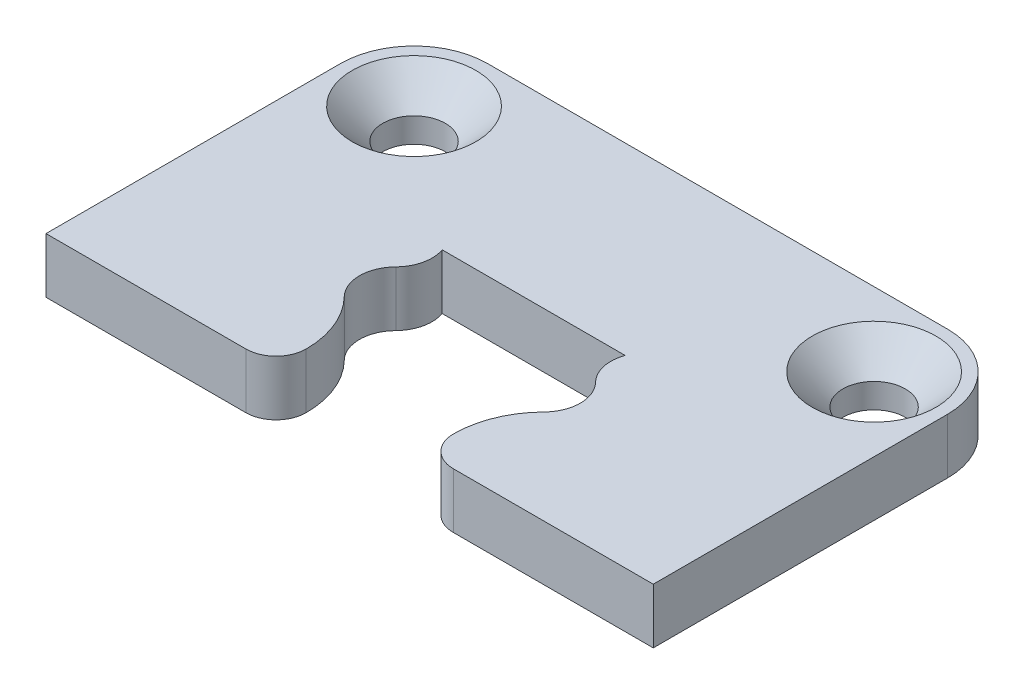
SolidWorks part; units mm, degrees
ref_plane "Front" through (0, 0, 0) normal (0, 0, 1) x (1, 0, 0)
ref_plane "Top" through (0, 0, 0) normal (0, 1, 0) x (1, 0, 0)
ref_plane "Right" through (0, 0, 0) normal (1, 0, 0) x (0, 0, -1)
sketch "Sketch1" plane through (0, 0, 0) normal (0, 1, 0) x (1, 0, 0)
  line L1 (-16.5, 20) -> (16.5, 20)
  line L2 (-16.5, 20) -> (-16.5, 0)
  line L3 (-16.5, 0) -> (-5.6369, 0)
  line L4 (16.5, 20) -> (16.5, 0)
  line L7 (5.6369, 0) -> (16.5, 0)
  line L8 (-5.6369, 0) -> (5.6369, 0) construction
  line L9 (0, 0) -> (0, 10) construction
  line L10 (-4.9708, 10) -> (4.9708, 10)
  line L11 (-4, 6.5359) -> (-4, 0) construction
  arc A0 (-5.4286, 5.1362) -> (-5.4286, 7.9356) centre (-4, 6.5359) cw
  arc A3 (-4, 1.6369) -> (-5.4286, 5.1362) centre (-9, 1.6369) ccw
  arc A4 (-5.4286, 7.9356) -> (-4.9708, 10) centre (-6.8571, 9.3353) ccw
  arc A7 (4, 1.6369) -> (5.4286, 5.1362) centre (9, 1.6369) cw
  arc A8 (5.4286, 5.1362) -> (5.4286, 7.9356) centre (4, 6.5359) ccw
  arc A9 (5.4286, 7.9356) -> (4.9708, 10) centre (6.8571, 9.3353) cw
  arc A10 (-5.4286, 7.9356) -> (-5, 8.2679) centre (-4, 6.5359) cw construction
  arc A11 (-5, 8.2679) -> (-4, 10) centre (-6, 10) ccw construction
  arc A12 (-5.6369, 0) -> (-4, 1.6369) centre (-5.6369, 1.6369) ccw
  arc A13 (5.6369, 0) -> (4, 1.6369) centre (5.6369, 1.6369) cw
  dimension "D3" = 5
  dimension "D4" = 2
  dimension "D6" = 10
  dimension "D1" = 20
  dimension "D2" = 33
  dimension "D5" = 8
extrude "Boss-Extrude1" add sketch "Sketch1" along normal blind 3
sketch "Sketch2" plane through (0, 0, 0) normal (0, 1, 0) x (1, 0, 0)
  line L0 (-12.5, 16) -> (12.5, 16) construction
  line L3 (0, 16) -> (0, 0) construction
  line L4 (16.5, 20) -> (-16.5, 20) construction
  dimension "D1" = 25
  dimension "D2" = 4
hole_wizard "CSK for M3 SFHCS1" positions "Sketch3" profile "Sketch4" countersink size "M3" standard "ANSI Metric"
sketch "Sketch3" plane through (0, 3, 0) normal (0, 1, 0) x (1, 0, 0)
  point P0 (12.5, 16)
  point P3 (-12.5, 16)
sketch "Sketch4" plane through (12.5, 3, -16) normal (1, 0, 0) x (0, 0, 1)
  line L0 (0, 0) -> (0, 11.0215)
  line L1 (0, 11.0215) -> (1.7, 10)
  line L2 (1.7, 10) -> (1.7, 1.66)
  line L3 (1.7, 1.66) -> (3.36, 0)
  line L5 (3.36, 0) -> (0, 0)
  line L6 (-1.7, 1.66) -> (-3.36, 0) construction
  line L10 (0, 11.0215) -> (-1.7, 10) construction
  line L11 (0, -6.35) -> (0, 107.95) construction
  dimension "Hole Dia." = 3.4
  dimension "Hole Depth" = 10
  dimension "Near C'Sink Dia." = 6.72
  dimension "Near C'Sink Angle" = 90
  dimension "Drill Angle" = 118
fillet "Fillet1" radius 4 2 edges at (16.5, 1.5, -20) (-16.5, 1.5, -20)
